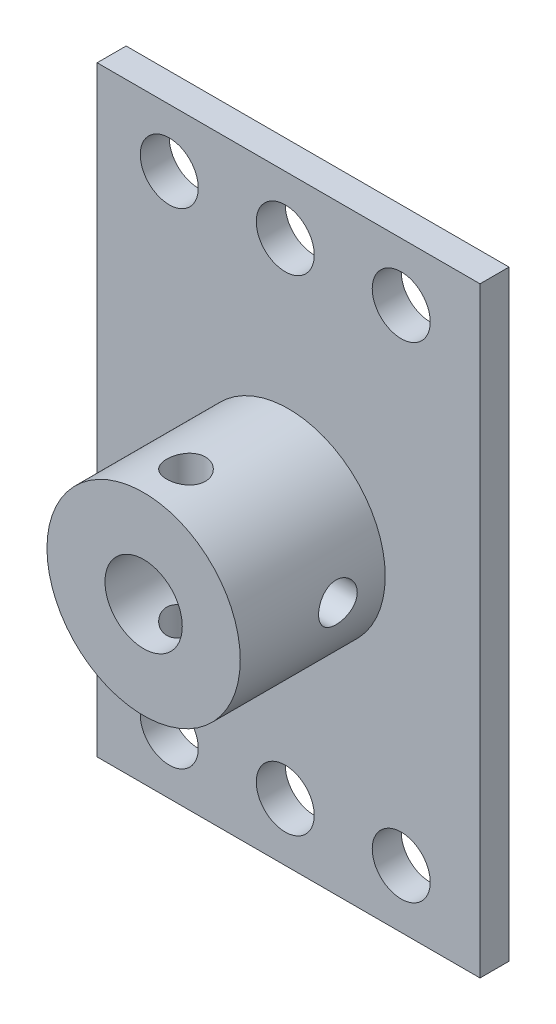
SolidWorks part; units mm, degrees
material "Bronce de aluminio"
ref_plane "Alzado" through (0, 0, 0) normal (0, 0, 1) x (1, 0, 0)
ref_plane "Planta" through (0, 0, 0) normal (0, 1, 0) x (1, 0, 0)
ref_plane "Vista lateral" through (0, 0, 0) normal (1, 0, 0) x (0, 0, -1)
sketch "Croquis1" plane through (0, 0, 0) normal (0, 0, 1) x (1, 0, 0)
  line L1 (9.026, -35.2154) -> (48.6445, -35.2154)
  line L2 (9.026, -35.2154) -> (9.026, 26.9909)
  line L3 (9.026, 26.9909) -> (48.6445, 26.9909)
  line L4 (48.6445, -35.2154) -> (48.6445, 26.9909)
  line L5 (9.026, -35.2154) -> (48.6445, 26.9909) construction
  line L6 (9.026, 26.9909) -> (48.6445, -35.2154) construction
  line L8 (48.6445, 26.9909) -> (8.6445, 26.9909) construction
  point P0 (9.026, -4.1122)
extrude "Saliente-Extruir1" add sketch "Croquis1" along normal blind 3
sketch "Croquis2" plane through (0, 0, 3) normal (0, 0, 1) x (1, 0, 0)
  line L0 (28.8353, 39.8289) -> (28.8353, -44.5107) construction
  line L1 (53.3452, -4.1122) -> (13.9316, -4.1122) construction
  line L2 (48.6445, 26.9909) -> (9.026, 26.9909) construction
  line L3 (9.026, -35.2154) -> (48.6445, -35.2154) construction
  line L4 (48.6445, -35.2154) -> (48.6445, 26.9909) construction
  line L5 (9.026, 26.9909) -> (9.026, -35.2154) construction
  circle A0 centre (28.8353, -4.1122) radius 10
  dimension "D1" = 20
extrude "Saliente-Extruir2" add sketch "Croquis2" along normal blind 15
sketch "Croquis3" plane through (0, 0, 18) normal (0, 0, 1) x (1, 0, 0)
  line L0 (28.8353, 33.0225) -> (28.8353, -45.5847) construction
  line L1 (51.3582, -4.1122) -> (15.3343, -4.1122) construction
  line L2 (9.026, 26.9909) -> (9.026, -35.2154) construction
  line L3 (48.6445, -35.2154) -> (48.6445, 26.9909) construction
  line L4 (9.026, -35.2154) -> (48.6445, -35.2154) construction
  line L5 (48.6445, 26.9909) -> (9.026, 26.9909) construction
  circle A0 centre (28.8353, -4.1122) radius 4
  dimension "D1" = 8
extrude "Cortar-Extruir1" cut sketch "Croquis3" against normal through all
sketch "Croquis5" plane through (0, 0, 0) normal (1, 0, 0) x (0, 0, -1)
  line L0 (-18, -4.1122) -> (-3, -4.1122) construction
  line L1 (-18, 5.8878) -> (-18, -14.1122) construction
  line L4 (-3, 5.8878) -> (-3, -14.1122) construction
  circle A0 centre (-7.8931, -4.1122) radius 2
  point P4 (-6.3538, -4.1122)
  point P5 (-7.0607, -4.1122)
  point P6 (-7.8931, -4.1122)
  point P8 (-10.5, -4.1122)
  dimension "D1" = 4
extrude "Cortar-Extruir3" cut sketch "Croquis5" against normal through all and the other way through all
sketch "Croquis6" plane through (0, 0, 0) normal (0, 0, -1) x (-1, 0, 0)
  circle A0 centre (-40.4901, -29.2154) radius 3
  circle A1 centre (-28.4901, -29.2154) radius 3
  circle A2 centre (-16.4901, -29.2154) radius 3
  circle A3 centre (-28.4901, 20.9909) radius 3
  circle A4 centre (-40.4901, 20.9909) radius 3
  circle A5 centre (-16.4901, 20.9909) radius 3
extrude "Cortar-Extruir4" cut sketch "Croquis6" against normal blind 10
sketch "Croquis7" plane through (0, 0, 0) normal (0, 1, 0) x (1, 0, 0)
  line L0 (28.8353, -4.3191) -> (28.8353, -14.2889) construction
  line L1 (18.8353, -9.8931) -> (18.8353, -18) construction
  line L2 (38.8353, -18) -> (38.8353, -9.8931) construction
  circle A0 centre (28.8353, -13.6158) radius 2
  point P8 (28.8353, -13.6158)
  dimension "D1" = 4
extrude "Cortar-Extruir5" cut sketch "Croquis7" against normal through all and the other way through all contours A0
